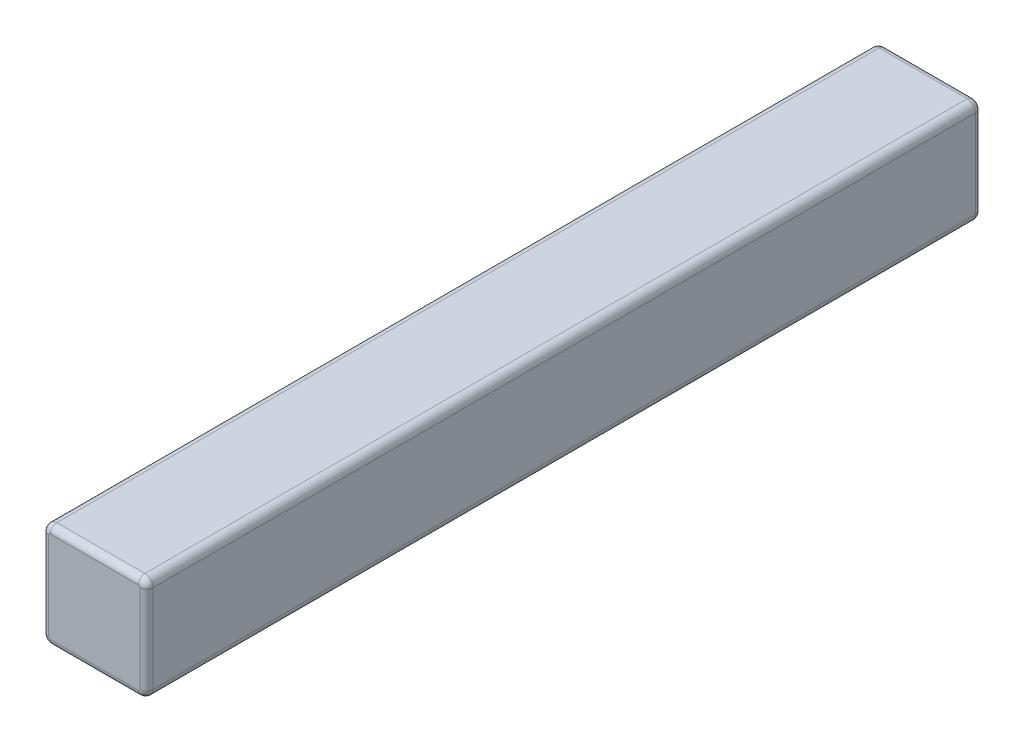
SolidWorks part; units mm, degrees
material "Plain Carbon Steel"
ref_plane "Front Plane" through (0, 0, 0) normal (0, 0, 1) x (1, 0, 0)
ref_plane "Top Plane" through (0, 0, 0) normal (0, 1, 0) x (1, 0, 0)
ref_plane "Right Plane" through (0, 0, 0) normal (1, 0, 0) x (0, 0, -1)
sketch "Sketch1" plane through (0, 0, 0) normal (0, 0, 1) x (1, 0, 0)
  line L1 (-1.3375, 1.5875) -> (1.3375, 1.5875)
  line L2 (-1.5875, 1.3375) -> (-1.5875, -1.3375)
  line L3 (-1.3375, -1.5875) -> (1.3375, -1.5875)
  line L4 (1.5875, 1.3375) -> (1.5875, -1.3375)
  line L5 (-1.5875, 1.5875) -> (1.5875, -1.5875) construction
  line L6 (-1.5875, -1.5875) -> (1.5875, 1.5875) construction
  arc A0 (-1.5875, -1.3375) -> (-1.3375, -1.5875) centre (-1.3375, -1.3375) ccw
  arc A1 (1.3375, -1.5875) -> (1.5875, -1.3375) centre (1.3375, -1.3375) ccw
  arc A2 (1.5875, 1.3375) -> (1.3375, 1.5875) centre (1.3375, 1.3375) ccw
  arc A3 (-1.3375, 1.5875) -> (-1.5875, 1.3375) centre (-1.3375, 1.3375) ccw
  point P0 (0, 0)
  dimension "D2" = 0.25
  dimension "D1" = 3.175
extrude "Boss-Extrude1" add sketch "Sketch1" along normal blind 25.4 contours L1 A2 L4 A1 L3 A0 L2 A3
fillet "Fillet1" radius 0.2 16 edges at (-1.5875, 0, 0) (-1.5143, -1.5143, 0) (0, -1.5875, 0) (1.5143, -1.5143, 0) (1.5875, 0, 0) (1.5143, 1.5143, 0) (0, 1.5875, 0) (-1.5143, 1.5143, 0) (0, 1.5875, 25.4) (1.5143, 1.5143, 25.4) (1.5875, 0, 25.4) (1.5143, -1.5143, 25.4) (0, -1.5875, 25.4) (-1.5143, -1.5143, 25.4) (-1.5875, 0, 25.4) (-1.5143, 1.5143, 25.4)
